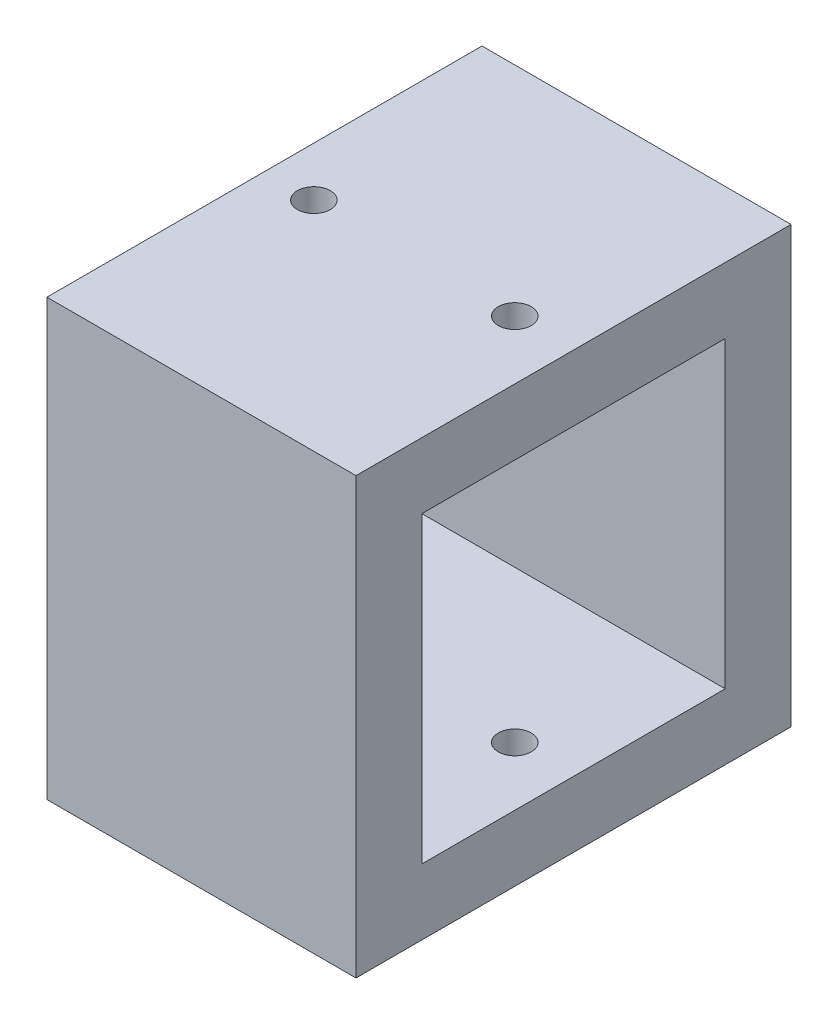
SolidWorks part; units mm, degrees
ref_plane "Front Plane" through (0, 0, 0) normal (0, 0, 1) x (1, 0, 0)
ref_plane "Top Plane" through (0, 0, 0) normal (0, 1, 0) x (1, 0, 0)
ref_plane "Right Plane" through (0, 0, 0) normal (1, 0, 0) x (0, 0, -1)
sketch "Sketch1" plane through (0, 0, 0) normal (1, 0, 0) x (0, 0, -1)
  line L13 (-14.8372, -8.9594) -> (18.7177, -8.9594)
  line L14 (-14.8372, -8.9594) -> (-14.8372, 24.5956)
  line L15 (-14.8372, 24.5956) -> (18.7177, 24.5956)
  line L16 (18.7177, -8.9594) -> (18.7177, 24.5956)
  line L17 (-14.8372, -8.9594) -> (18.7177, 24.5956) construction
  line L18 (-14.8372, 24.5956) -> (18.7177, -8.9594) construction
  line L19 (-9.7572, -3.8794) -> (13.6377, -3.8794)
  line L20 (-9.7572, -3.8794) -> (-9.7572, 19.5156)
  line L21 (-9.7572, 19.5156) -> (13.6377, 19.5156)
  line L22 (13.6377, -3.8794) -> (13.6377, 19.5156)
  line L23 (-9.7572, -3.8794) -> (13.6377, 19.5156) construction
  line L24 (-9.7572, 19.5156) -> (13.6377, -3.8794) construction
  point P0 (1.9403, 7.8181)
  point P5 (1.9403, 7.8181)
  dimension "D1" = 33.555
  dimension "D2" = 33.555
  dimension "D3" = 5.08
  dimension "D4" = 5.08
extrude "Boss-Extrude1" add sketch "Sketch1" along normal blind 23.8378
sketch "Sketch2" plane through (0, -8.9594, 0) normal (0, -1, 0) x (1, 0, 0)
  line L0 (0, -1.9403) -> (23.8378, -1.9403) construction
  line L1 (0, 14.8372) -> (0, -18.7177) construction
  line L2 (23.8378, 14.8372) -> (23.8378, -18.7177) construction
  circle A0 centre (3.81, -1.9403) radius 1.27
  circle A1 centre (19.304, -1.9403) radius 1.27
  dimension "D1" = 2.54
  dimension "D2" = 2.54
  dimension "D3" = 15.494
  dimension "D4" = 3.81
extrude "Cut-Extrude1" cut sketch "Sketch2" against normal through all
